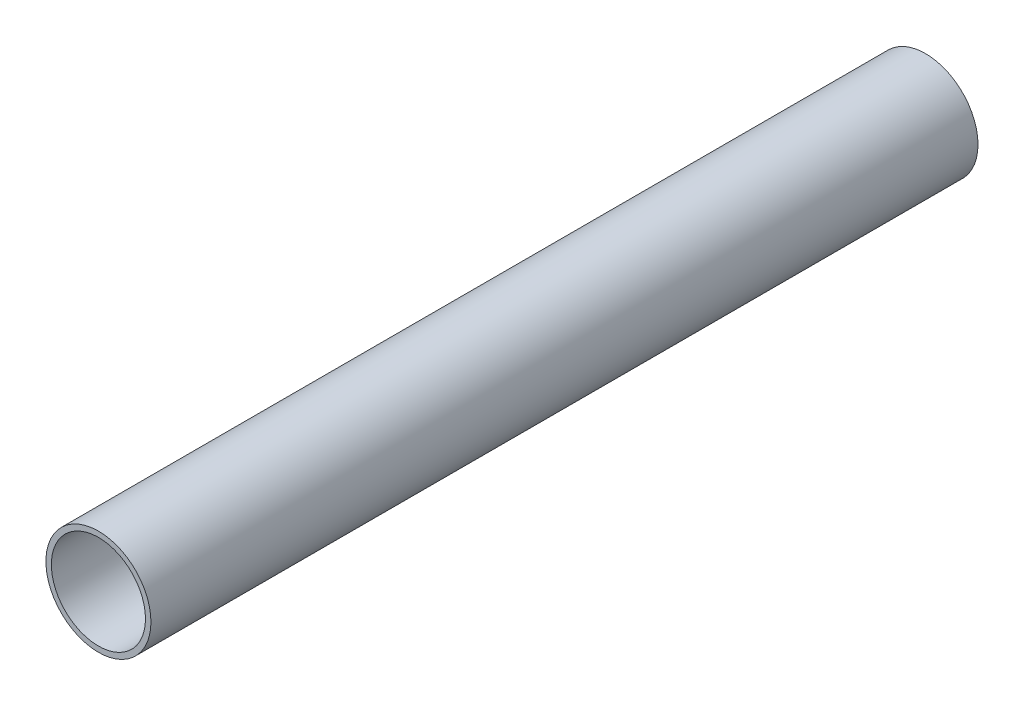
SolidWorks part; units mm, degrees
ref_plane "Front Plane" through (0, 0, 0) normal (0, 0, 1) x (1, 0, 0)
ref_plane "Top Plane" through (0, 0, 0) normal (0, 1, 0) x (1, 0, 0)
ref_plane "Right Plane" through (0, 0, 0) normal (1, 0, 0) x (0, 0, -1)
sketch "Sketch1" plane through (0, 0, 0) normal (0, 0, 1) x (1, 0, 0)
  circle A0 centre (0, 0) radius 15.875
  circle A1 centre (0, 0) radius 14.224
  dimension "D1" = 31.75
  dimension "D2" = 28.448
extrude "Boss-Extrude1" add sketch "Sketch1" along normal blind 250
